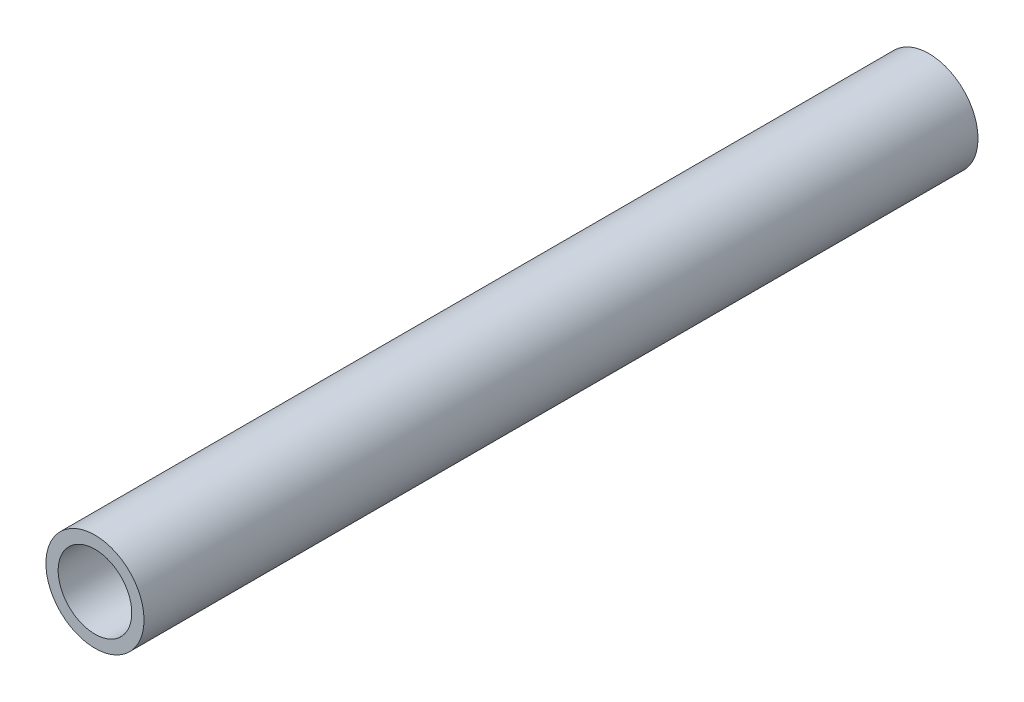
SolidWorks part; units mm, degrees
ref_plane "Front Plane" through (0, 0, 0) normal (0, 0, 1) x (1, 0, 0)
ref_plane "Top Plane" through (0, 0, 0) normal (0, 1, 0) x (1, 0, 0)
ref_plane "Right Plane" through (0, 0, 0) normal (1, 0, 0) x (0, 0, -1)
sketch "Sketch1" plane through (0, 0, 0) normal (0, 0, 1) x (1, 0, 0)
  circle A0 centre (0, 0) radius 9.525
  circle A1 centre (0, 0) radius 12.7
  dimension "D1" = 19.05
  dimension "D2" = 25.4
extrude "Boss-Extrude1" add sketch "Sketch1" along normal blind 215.9
